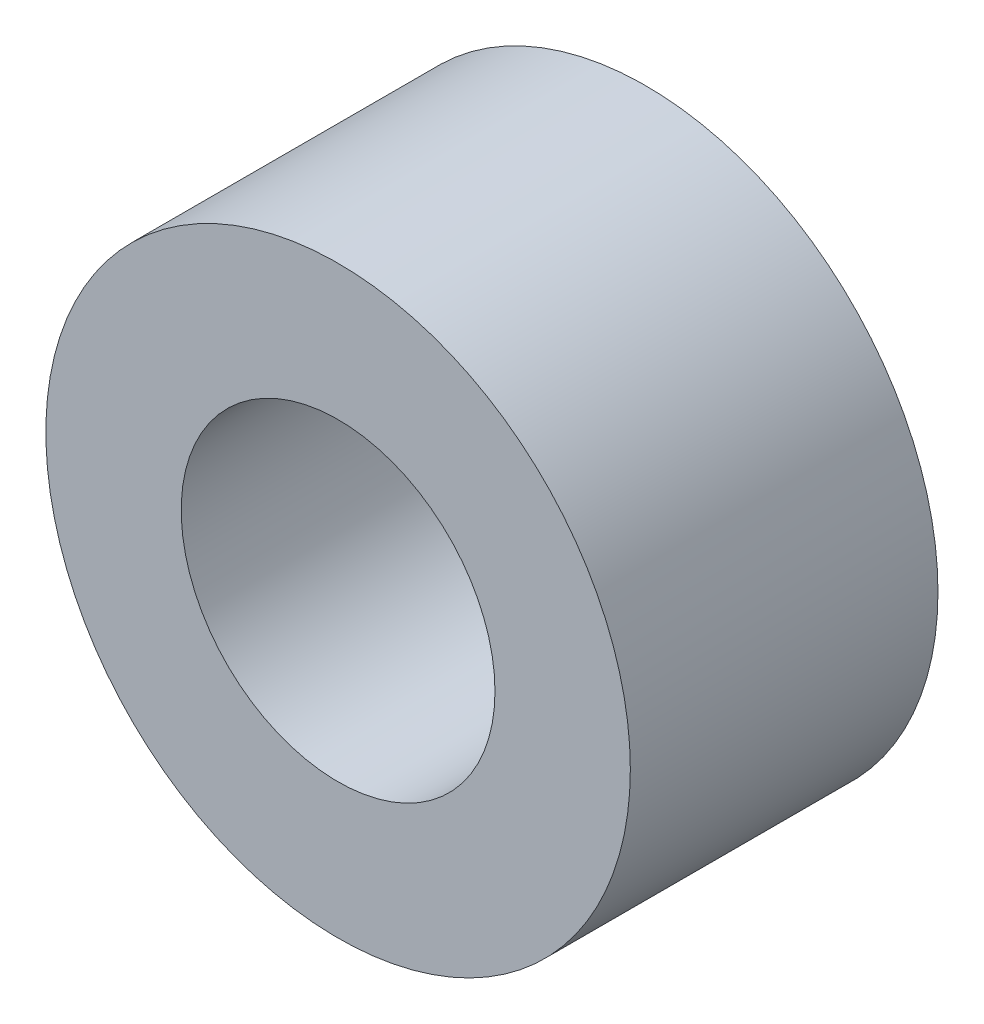
SolidWorks part; units mm, degrees
ref_plane "前视基准面" through (0, 0, 0) normal (0, 0, 1) x (1, 0, 0)
ref_plane "上视基准面" through (0, 0, 0) normal (0, 1, 0) x (1, 0, 0)
ref_plane "右视基准面" through (0, 0, 0) normal (1, 0, 0) x (0, 0, -1)
other "Configuration Table"
sketch "草图1" plane through (0, 0, 0) normal (0, 0, 1) x (1, 0, 0)
  circle A0 centre (0, 0) radius 4.75
  circle A1 centre (0, 0) radius 2.55
  dimension "D1" = 9.5
  dimension "D2" = 5.1
extrude "凸台-拉伸1" add sketch "草图1" along normal blind 5
